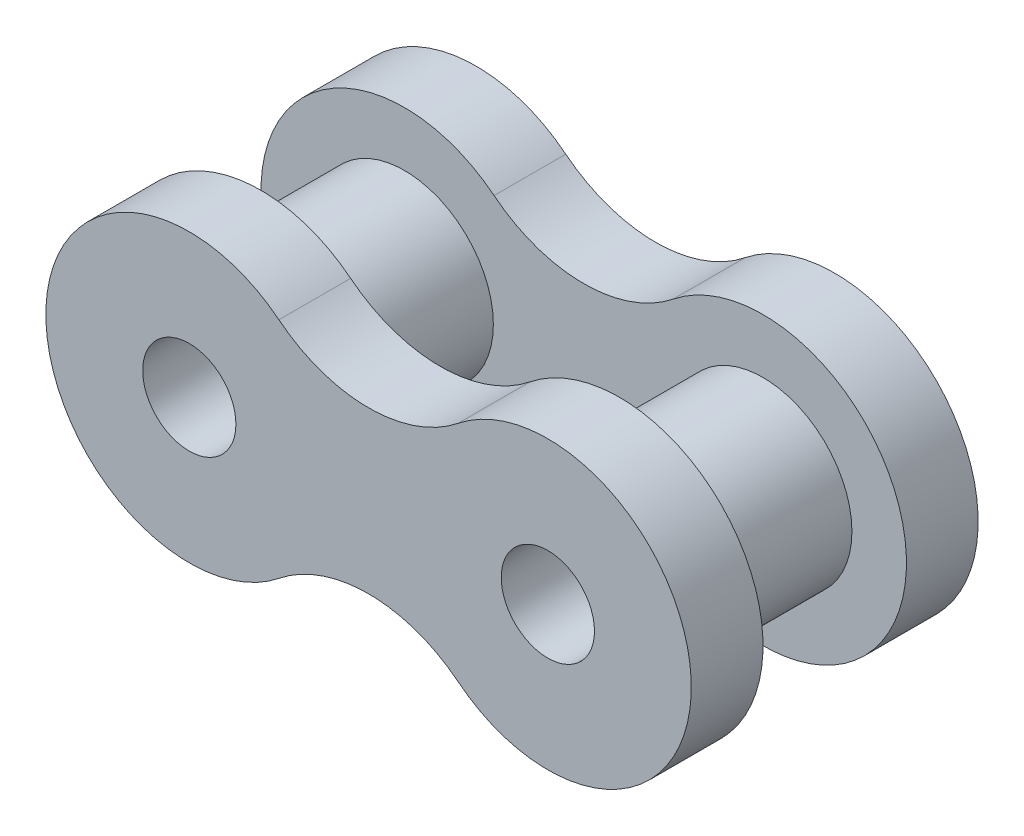
SolidWorks part; units mm, degrees
material "Chromium Copper, UNS C18200"
ref_plane "Front Plane" through (0, 0, 0) normal (0, 0, 1) x (1, 0, 0)
ref_plane "Top Plane" through (0, 0, 0) normal (0, 1, 0) x (1, 0, 0)
ref_plane "Right Plane" through (0, 0, 0) normal (1, 0, 0) x (0, 0, -1)
sketch "Sketch1" plane through (0, 0, 0) normal (0, 0, 1) x (1, 0, 0)
  line L0 (0, 0) -> (0, 3.0668) construction
  circle A0 centre (3.175, 0) radius 1.5748
  circle A1 centre (-3.175, 0) radius 1.5748
  dimension "D1" = 6.35
  dimension "D2" = 3.1496
extrude "Boss-Extrude1" add sketch "Sketch1" along normal mid plane 2.54
sketch "Sketch2" plane through (0, 0, 1.27) normal (0, 0, 1) x (1, 0, 0)
  line L0 (0, 0) -> (0, 1.4256) construction
  line L1 (0, 0) -> (3.175, 0) construction
  arc A0 (1.5875, -1.9828) -> (1.5875, 1.9828) centre (3.175, 0) ccw
  arc A1 (-1.5875, 1.9828) -> (-1.5875, -1.9828) centre (-3.175, 0) ccw
  arc A2 (-1.5875, 1.9828) -> (1.5875, 1.9828) centre (0, 3.9656) ccw
  arc A3 (1.5875, -1.9828) -> (-1.5875, -1.9828) centre (0, -3.9656) ccw
  dimension "D1" = 5.08
  dimension "D2" = 5.08
extrude "Boss-Extrude2" add sketch "Sketch2" along normal blind 1.27
mirror "Mirror1" about plane through (0, 0, 0) normal (0, 0, 1) of "Boss-Extrude2"
sketch "Sketch3" plane through (0, 0, 2.54) normal (0, 0, 1) x (1, 0, 0)
  line L0 (0, 0) -> (0, 1.4256) construction
  arc A0 (-1.5875, 1.9828) -> (1.5875, 1.9828) centre (0, 3.9656) ccw construction
  circle A1 centre (3.175, 0) radius 0.8255
  circle A2 centre (-3.175, 0) radius 0.8255
  dimension "D1" = 1.651
extrude "Cut-Extrude1" cut sketch "Sketch3" against normal up to surface (5.08 mm away) up to face at (0, 0, -2.54)
